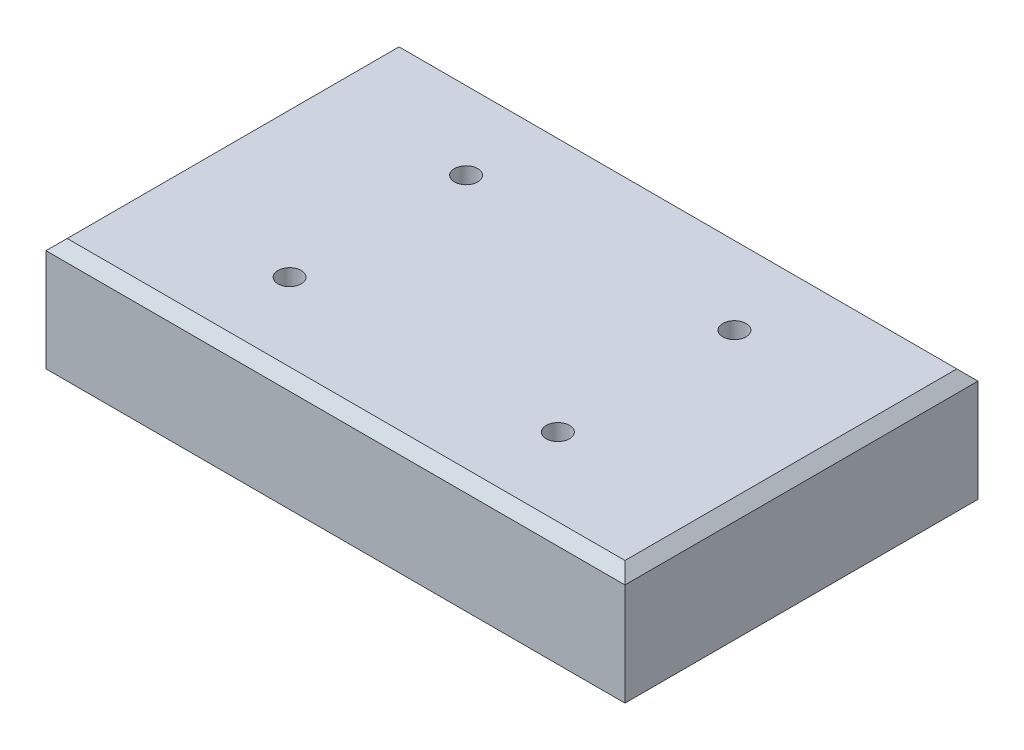
SolidWorks part; units mm, degrees
ref_plane "Front Plane" through (0, 0, 0) normal (0, 0, 1) x (1, 0, 0)
ref_plane "Top Plane" through (0, 0, 0) normal (0, 1, 0) x (1, 0, 0)
ref_plane "Right Plane" through (0, 0, 0) normal (1, 0, 0) x (0, 0, -1)
sketch "Sketch2" plane through (0, 0, 0) normal (0, 1, 0) x (1, 0, 0)
  line L1 (-41, 25) -> (41, 25)
  line L2 (-41, 25) -> (-41, -25)
  line L3 (-41, -25) -> (41, -25)
  line L4 (41, 25) -> (41, -25)
  line L5 (-41, 25) -> (41, -25) construction
  line L6 (-41, -25) -> (41, 25) construction
  point P0 (0, 0)
  dimension "D1" = 50
  dimension "D2" = 82
extrude "Boss-Extrude1" add sketch "Sketch2" along normal blind 16
hole_wizard "M4 Tapped Hole1" positions "Sketch4" profile "Sketch3" tap size "M4" standard "DIN"
sketch "Sketch4" plane through (0, 16, 0) normal (0, 1, 0) x (1, 0, 0)
  line L0 (0, 25) -> (0, 0) construction
  line L1 (41, 25) -> (-41, 25) construction
  line L2 (0, 0) -> (-41, 0) construction
  line L3 (-41, 25) -> (-41, -25) construction
  point P2 (-19, 12.5)
  point P4 (-19, -12.5)
  point P6 (19, -12.5)
  point P8 (19, 12.5)
  dimension "D1" = 38
  dimension "D2" = 25
sketch "Sketch3" plane through (-19, 16, -12.5) normal (1, 0, 0) x (0, 0, 1)
  line L0 (0, 0) -> (0, 8.9914)
  line L1 (0, 8.9914) -> (1.65, 8)
  line L2 (1.65, 8) -> (1.65, 0)
  line L5 (1.65, 0) -> (0, 0)
  line L10 (0, 8.9914) -> (-1.65, 8) construction
  line L11 (0, -6.35) -> (0, 107.95) construction
  dimension "Tap Drill Dia." = 3.3
  dimension "Tap Drill Depth" = 8
  dimension "Drill Angle" = 118
cosmetic thread "Hole Thread1" parameters "D1"=6, "D2"=4
cosmetic thread "Hole Thread2" parameters "D1"=6, "D2"=4
cosmetic thread "Hole Thread3" parameters "D1"=6, "D2"=4
cosmetic thread "Hole Thread4" parameters "D1"=6, "D2"=4
chamfer "Chamfer1" distance 1.5 angle 45 4 edges at (0, 16, -25) (41, 16, 0) (0, 16, 25) (-41, 16, 0)
